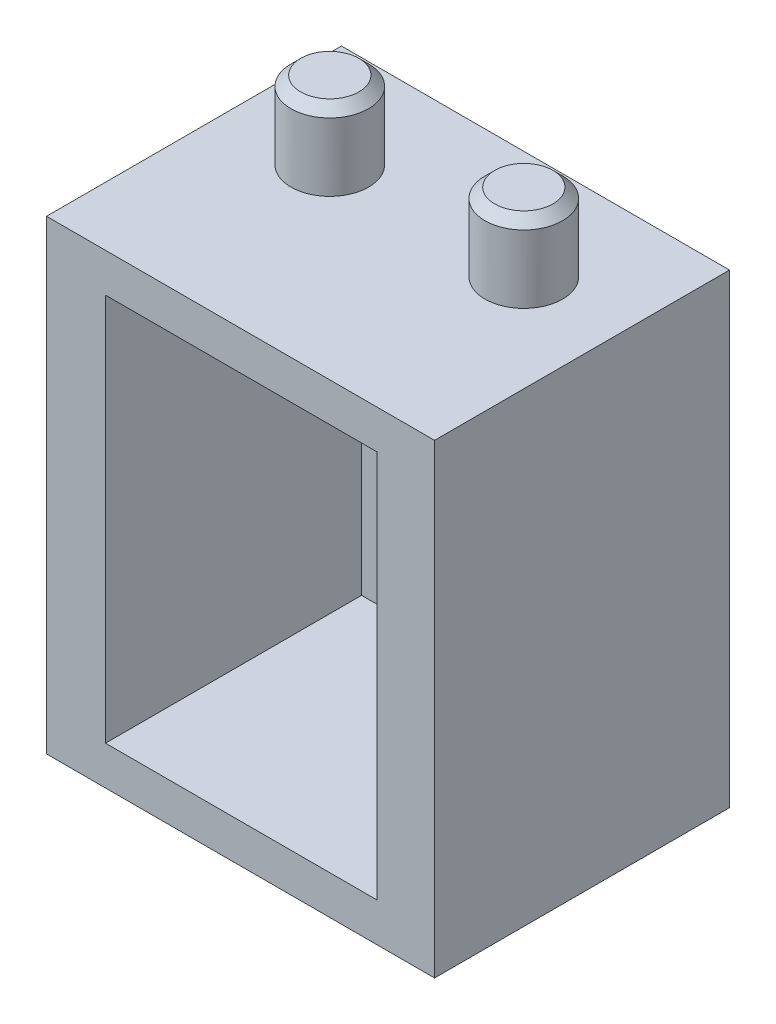
SolidWorks part; units mm, degrees
ref_plane "Front Plane" through (0, 0, 0) normal (0, 0, 1) x (1, 0, 0)
ref_plane "Top Plane" through (0, 0, 0) normal (0, 1, 0) x (1, 0, 0)
ref_plane "Right Plane" through (0, 0, 0) normal (1, 0, 0) x (0, 0, -1)
sketch "Sketch2" plane through (0, 0, 0) normal (0, 0, 1) x (1, 0, 0)
  line L1 (0, 0) -> (63.5, 0)
  line L2 (0, 0) -> (0, 76.2)
  line L3 (0, 76.2) -> (63.5, 76.2)
  line L4 (63.5, 0) -> (63.5, 76.2)
  dimension "D1" = 76.2
  dimension "D2" = 63.5
extrude "Boss-Extrude1" add sketch "Sketch2" along normal blind 48.26
sketch "Sketch3" plane through (0, 0, 48.26) normal (0, 0, 1) x (1, 0, 0)
  line L0 (0, 0) -> (63.5, 0) construction
  line L1 (9.652, 69.85) -> (54.102, 69.85)
  line L2 (9.652, 69.85) -> (9.652, 6.35)
  line L3 (9.652, 6.35) -> (54.102, 6.35)
  line L4 (54.102, 69.85) -> (54.102, 6.35)
  line L5 (0, 76.2) -> (0, 0) construction
  dimension "D1" = 44.45
  dimension "D2" = 63.5
  dimension "D3" = 6.35
  dimension "D4" = 9.652
extrude "Cut-Extrude1" cut sketch "Sketch3" against normal offset from surface (41.91 mm away) 6.35 up to face at (31.75, 38.1, 0)
sketch "Sketch4" plane through (0, 0, 6.35) normal (0, 0, 1) x (1, 0, 0)
  line L0 (9.652, 6.35) -> (54.102, 6.35) construction
  line L1 (25.527, 6.35) -> (38.227, 6.35)
  line L2 (25.527, 6.35) -> (25.527, 12.7)
  line L3 (25.527, 12.7) -> (38.227, 12.7)
  line L4 (38.227, 6.35) -> (38.227, 12.7)
  line L5 (31.877, 69.85) -> (31.877, 6.35) construction
  line L6 (54.102, 69.85) -> (9.652, 69.85) construction
  line L7 (16.383, 64.1985) -> (16.383, 12.0015) construction
  line L8 (18.2626, 64.1985) -> (18.2626, 12.0015)
  line L9 (14.5034, 64.1985) -> (14.5034, 12.0015)
  line L10 (47.371, 64.1985) -> (47.371, 12.0015) construction
  line L11 (49.2506, 64.1985) -> (49.2506, 12.0015)
  line L12 (45.4914, 64.1985) -> (45.4914, 12.0015)
  line L13 (9.652, 38.1) -> (54.102, 38.1) construction
  line L14 (9.652, 69.85) -> (9.652, 6.35) construction
  line L15 (54.102, 6.35) -> (54.102, 69.85) construction
  arc A0 (18.2626, 64.1985) -> (14.5034, 64.1985) centre (16.383, 64.1985) ccw
  arc A1 (14.5034, 12.0015) -> (18.2626, 12.0015) centre (16.383, 12.0015) ccw
  arc A2 (49.2506, 64.1985) -> (45.4914, 64.1985) centre (47.371, 64.1985) ccw
  arc A3 (45.4914, 12.0015) -> (49.2506, 12.0015) centre (47.371, 12.0015) ccw
  point P10 (31.877, 12.7)
  point P13 (16.383, 38.1)
  point P20 (47.371, 38.1)
  dimension "D4" = 1.8796
  dimension "D1" = 12.7
  dimension "D2" = 6.35
  dimension "D3" = 30.988
  dimension "D5" = 52.197
  dimension "D6" = 15.494
extrude "Cut-Extrude2" cut sketch "Sketch4" against normal through all both and the other way through all
sketch "Sketch5" plane through (0, 76.2, 0) normal (0, 1, 0) x (1, 0, 0)
  line L0 (63.5, -35.56) -> (0, -35.56) construction
  line L1 (63.5, -48.26) -> (63.5, 0) construction
  line L2 (0, -48.26) -> (0, 0) construction
  line L3 (63.5, -48.26) -> (0, -48.26) construction
  line L4 (0, -35.56) -> (0, 0) construction
  line L5 (0, -17.78) -> (63.5, -17.78) construction
  line L6 (31.75, -35.56) -> (31.75, 0) construction
  line L7 (63.5, 0) -> (0, 0) construction
  line L8 (31.75, -17.78) -> (0, -17.78) construction
  circle A0 centre (15.875, -17.78) radius 6.35
  circle A1 centre (47.625, -17.78) radius 6.35
  point P17 (15.875, -17.78)
  dimension "D2" = 12.7
  dimension "D1" = 12.7
extrude "Boss-Extrude2" add sketch "Sketch5" along normal blind 12.7
chamfer "Chamfer1" distance 1.5875 angle 45 2 edges at (15.875, 88.9, 24.13) (47.625, 88.9, 24.13)
